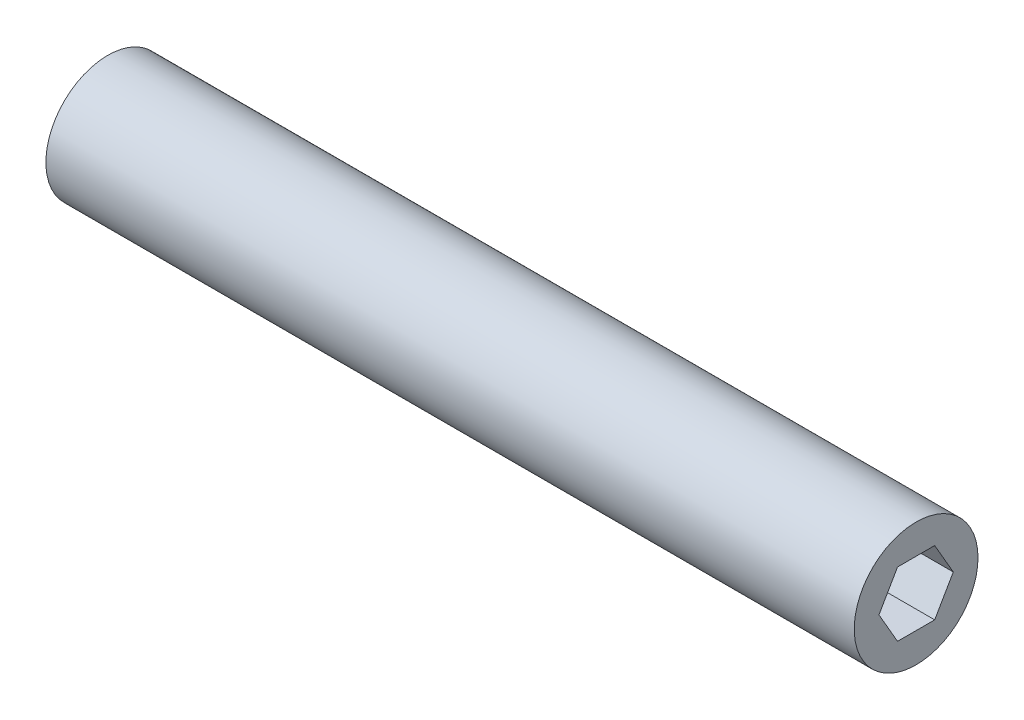
SolidWorks part; units mm, degrees
ref_plane "Front Plane" through (0, 0, 0) normal (0, 0, 1) x (1, 0, 0)
ref_plane "Top Plane" through (0, 0, 0) normal (0, 1, 0) x (1, 0, 0)
ref_plane "Right Plane" through (0, 0, 0) normal (1, 0, 0) x (0, 0, -1)
sketch "Sketch1" plane through (0, 0, 0) normal (1, 0, 0) x (0, 0, -1)
  line L1 (7.6256, 0) -> (3.8128, 6.604)
  line L2 (3.8128, 6.604) -> (-3.8128, 6.604)
  line L3 (-3.8128, 6.604) -> (-7.6256, 0)
  line L4 (-7.6256, 0) -> (-3.8128, -6.604)
  line L5 (-3.8128, -6.604) -> (3.8128, -6.604)
  line L6 (3.8128, -6.604) -> (7.6256, 0)
  circle A0 centre (0, 0) radius 6.604 construction
  circle A1 centre (0, 0) radius 12.7
  dimension "D1" = 13.208
  dimension "D2" = 25.4
extrude "Boss-Extrude1" add sketch "Sketch1" along normal blind 165.8938
